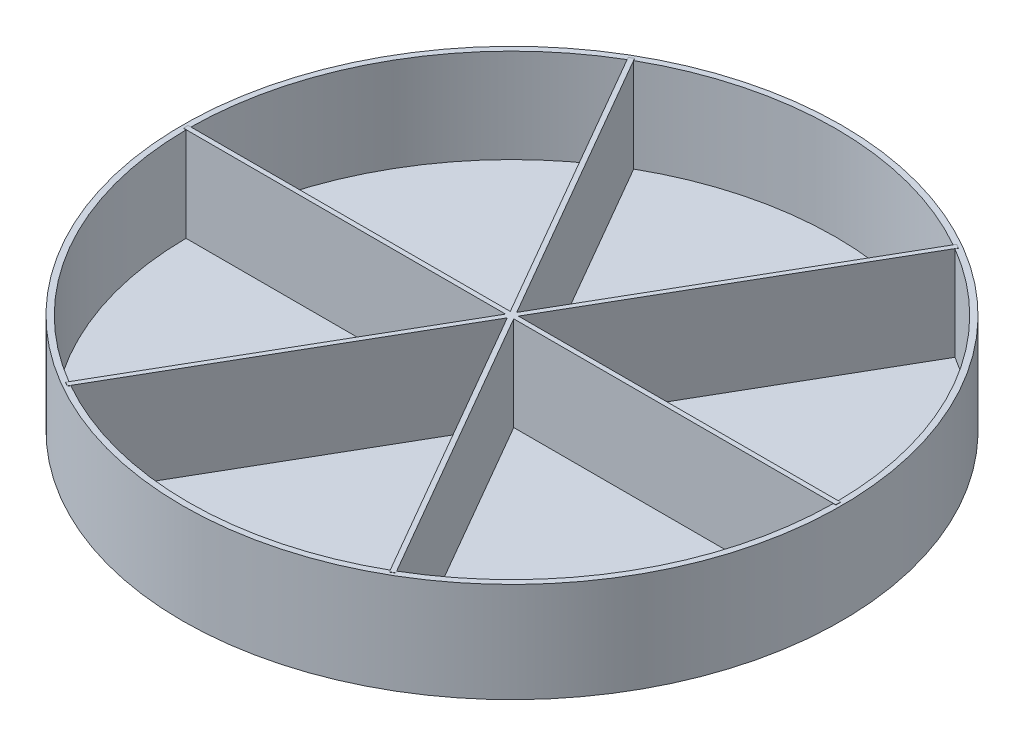
SolidWorks part; units mm, degrees
ref_plane "Front Plane" through (0, 0, 0) normal (0, 0, 1) x (1, 0, 0)
ref_plane "Top Plane" through (0, 0, 0) normal (0, 1, 0) x (1, 0, 0)
ref_plane "Right Plane" through (0, 0, 0) normal (1, 0, 0) x (0, 0, -1)
sketch "Sketch1" plane through (0, 0, 0) normal (0, 1, 0) x (1, 0, 0)
  circle A0 centre (0, 0) radius 177.8
  dimension "D1" = 355.6
extrude "Boss-Extrude1" add sketch "Sketch1" along normal blind 53.848
sketch "Sketch2" plane through (0, 53.848, 0) normal (0, 1, 0) x (1, 0, 0)
  circle A2 centre (0, 0) radius 174.625
  circle A3 centre (0, 0) radius 174.625
  dimension "D1" = 3.175
extrude "Cut-Extrude1" cut sketch "Sketch2" against normal offset from surface (50.673 mm away) 3.175 up to face at (0, 0, 177.8)
sketch "Sketch3" plane through (0, 3.175, 0) normal (0, 1, 0) x (1, 0, 0)
  line L0 (87.9882, 152.4) -> (-87.9882, -152.4)
  line L1 (-175.9764, 0) -> (-87.9882, -152.4) construction
  line L2 (-87.9882, -152.4) -> (87.9882, -152.4) construction
  line L3 (87.9882, -152.4) -> (175.9764, 0) construction
  line L4 (175.9764, 0) -> (87.9882, 152.4) construction
  line L5 (87.9882, 152.4) -> (-87.9882, 152.4) construction
  line L6 (-87.9882, 152.4) -> (-175.9764, 0) construction
  line L7 (-87.9882, 152.4) -> (87.9882, -152.4)
  line L8 (175.9764, 0) -> (-175.9764, 0)
  circle A0 centre (0, 0) radius 152.4 construction
  dimension "D1" = 304.8
extrude "Extrude-Thin1" add sketch "Sketch3" along normal blind 50.8 thin thin type mid plane wall 2.54
